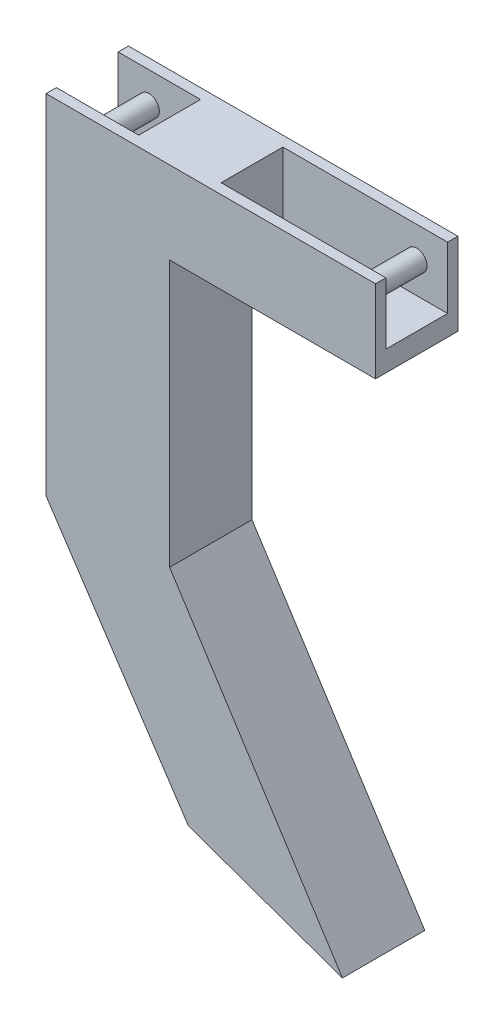
SolidWorks part; units mm, degrees
material "AISI 1020"
ref_plane "Front Plane" through (0, 0, 0) normal (0, 0, 1) x (1, 0, 0)
ref_plane "Top Plane" through (0, 0, 0) normal (0, 1, 0) x (1, 0, 0)
ref_plane "Right Plane" through (0, 0, 0) normal (1, 0, 0) x (0, 0, -1)
sketch "Sketch1" plane through (0, 0, 0) normal (0, 0, 1) x (1, 0, 0)
  line L0 (106.6667, 22.2154) -> (106.6667, 62.2154)
  line L1 (106.6667, 62.2154) -> (-53.3333, 62.2154)
  line L2 (-53.3333, 62.2154) -> (-53.3333, -107.0085)
  line L3 (-53.3333, -107.0085) -> (15.7538, -211.2)
  line L4 (15.7538, -211.2) -> (90.5846, -237.7846)
  line L5 (90.5846, -237.7846) -> (6.6667, -107.0085)
  line L6 (6.6667, -107.0085) -> (6.6667, 22.2154)
  line L7 (6.6667, 22.2154) -> (106.6667, 22.2154)
  dimension "D1" = 160
  dimension "D2" = 40
  dimension "D3" = 300
  dimension "D4" = 100
extrude "Boss-Extrude2" add sketch "Sketch1" along normal blind 40
sketch "Sketch2" plane through (0, 62.2154, 0) normal (0, 1, 0) x (1, 0, 0)
  line L0 (-53.3333, -20) -> (-33.3333, -20) construction
  line L1 (-53.3333, -40) -> (-53.3333, 0) construction
  line L3 (-53.3333, -5) -> (-13.3333, -5)
  line L4 (-53.3333, -5) -> (-53.3333, -35)
  line L5 (-53.3333, -35) -> (-13.3333, -35)
  line L6 (-13.3333, -5) -> (-13.3333, -35)
  line L7 (-53.3333, -5) -> (-13.3333, -35) construction
  line L8 (-53.3333, -35) -> (-13.3333, -5) construction
  dimension "D2" = 40
  dimension "D3" = 30
extrude "Cut-Extrude1" cut sketch "Sketch2" against normal blind 30
sketch "Sketch3" plane through (0, 0, 5) normal (0, 0, 1) x (1, 0, 0)
  line L0 (-53.3333, 47.2154) -> (-38.3333, 47.2154) construction
  line L1 (-53.3333, 32.2154) -> (-53.3333, 62.2154) construction
  circle A0 centre (-38.3333, 47.2154) radius 5
  dimension "D2" = 10
  dimension "D1" = 15
extrude "Boss-Extrude3" add sketch "Sketch3" along normal blind 30
sketch "Sketch4" plane through (0, 62.2154, 0) normal (0, 1, 0) x (1, 0, 0)
  line L0 (106.6667, -20) -> (26.6667, -20) construction
  line L1 (106.6667, -40) -> (106.6667, 0) construction
  line L3 (26.6667, -5) -> (106.6667, -5)
  line L4 (26.6667, -5) -> (26.6667, -35)
  line L5 (26.6667, -35) -> (106.6667, -35)
  line L6 (106.6667, -5) -> (106.6667, -35)
  line L7 (26.6667, -5) -> (106.6667, -35) construction
  line L8 (26.6667, -35) -> (106.6667, -5) construction
  point P4 (66.6667, -20)
  dimension "D1" = 80
  dimension "D2" = 30
extrude "Cut-Extrude2" cut sketch "Sketch4" against normal blind 30
sketch "Sketch5" plane through (0, 0, 5) normal (0, 0, 1) x (1, 0, 0)
  line L0 (106.6667, 47.2154) -> (91.6667, 47.2154) construction
  line L1 (106.6667, 32.2154) -> (106.6667, 62.2154) construction
  circle A0 centre (91.6667, 47.2154) radius 5
  dimension "D2" = 10
  dimension "D1" = 15
extrude "Boss-Extrude4" add sketch "Sketch5" along normal blind 30
